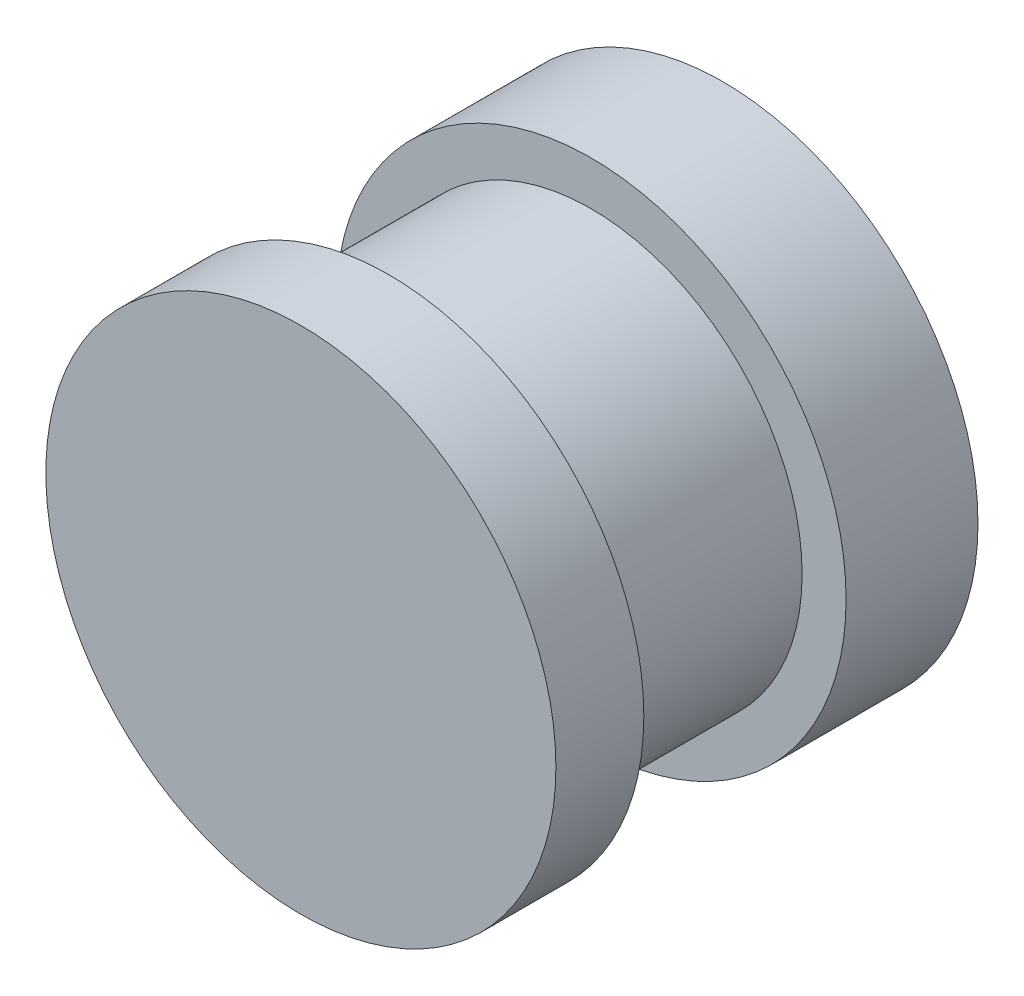
SolidWorks part; units mm, degrees
other "Детальный элемент1"
ref_plane "Спереди" through (0, 0, 0) normal (0, 0, 1) x (1, 0, 0)
ref_plane "Сверху" through (0, 0, 0) normal (0, 1, 0) x (1, 0, 0)
ref_plane "Справа" through (0, 0, 0) normal (1, 0, 0) x (0, 0, -1)
sketch "Эскиз1" plane through (0, 0, 0) normal (0, 0, 1) x (1, 0, 0)
  circle A0 centre (0, 0) radius 2.9
  dimension "D1" = 5.8
extrude "Бобышка-Вытянуть1" add sketch "Эскиз1" along normal blind 1.5
sketch "Эскиз2" plane through (0, 0, 1.5) normal (0, 0, 1) x (1, 0, 0)
  circle A0 centre (0, 0) radius 2.4
  dimension "D1" = 4.8
extrude "Бобышка-Вытянуть2" add sketch "Эскиз2" along normal blind 2.3
sketch "Эскиз3" plane through (0, 0, 3.8) normal (0, 0, 1) x (1, 0, 0)
  circle A0 centre (0, 0) radius 2.9
  circle A1 centre (0, 0) radius 2.9 construction
extrude "Бобышка-Вытянуть3" add sketch "Эскиз3" along normal blind 1
